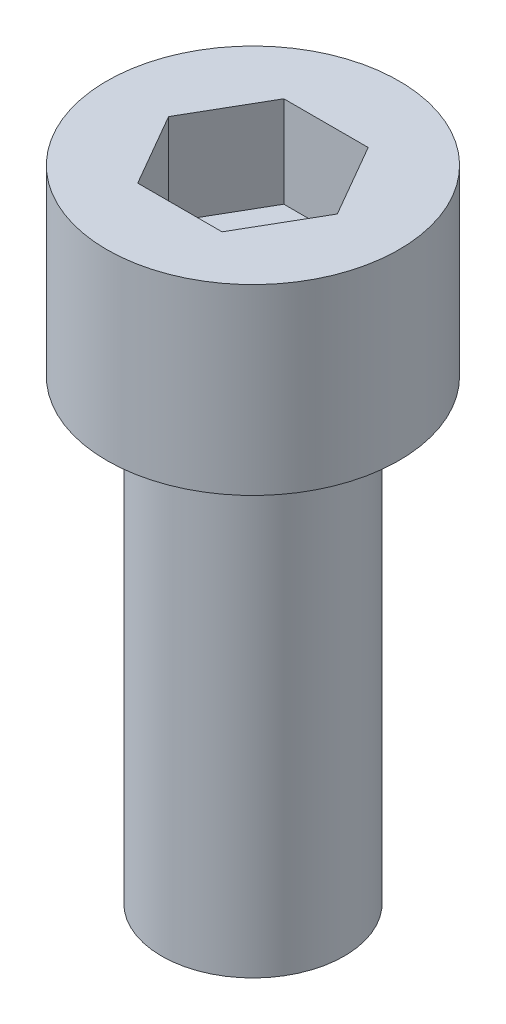
SolidWorks part; units mm, degrees
material "AISI 304"
ref_plane "Front Plane" through (0, 0, 0) normal (0, 0, 1) x (1, 0, 0)
ref_plane "Top Plane" through (0, 0, 0) normal (0, 1, 0) x (1, 0, 0)
ref_plane "Right Plane" through (0, 0, 0) normal (1, 0, 0) x (0, 0, -1)
sketch "Sketch1" plane through (0, 0, 0) normal (0, 0, 1) x (1, 0, 0)
  line L0 (0, 61.6916) -> (0, -59.3578) construction
  line L1 (0, -25) -> (5, -25)
  line L2 (5, -25) -> (5, 0)
  line L3 (5, 0) -> (8, 0)
  line L4 (8, 0) -> (8, 10)
  line L5 (8, 10) -> (0, 10)
  line L6 (0, 10) -> (0, -25)
  dimension "D1" = 25
  dimension "D2" = 16
  dimension "D3" = 10
  dimension "D4" = 10
revolve "Revolve1" add sketch "Sketch1" angle 360 about L0
sketch "Sketch2" plane through (0, 10, 0) normal (0, 1, 0) x (-1, 0, 0)
  line L1 (-2.3094, -4) -> (2.3094, -4)
  line L2 (2.3094, -4) -> (4.6188, 0)
  line L3 (4.6188, 0) -> (2.3094, 4)
  line L4 (2.3094, 4) -> (-2.3094, 4)
  line L5 (-2.3094, 4) -> (-4.6188, 0)
  line L6 (-4.6188, 0) -> (-2.3094, -4)
  circle A0 centre (0, 0) radius 4 construction
  dimension "D1" = 8
extrude "Cut-Extrude1" cut sketch "Sketch2" against normal blind 5
sketch "Sketch3" plane through (0, 0, 0) normal (0, 0, 1) x (1, 0, 0)
  line L0 (0, 0) -> (0, -16.4485) construction
  line L1 (-5, 0) -> (5, 0) construction
  line L3 (0, 0) -> (5.5, 0)
  line L4 (0, 0) -> (0, -4.9368)
  line L5 (0, -4.9368) -> (5.5, -1.5)
  line L6 (5.5, 0) -> (5.5, -1.5)
  dimension "D1" = 58
  dimension "D2" = 1.5
  dimension "D3" = 11
revolve "O-ring relief in hole" add sketch "Sketch3" angle 360 about L0
